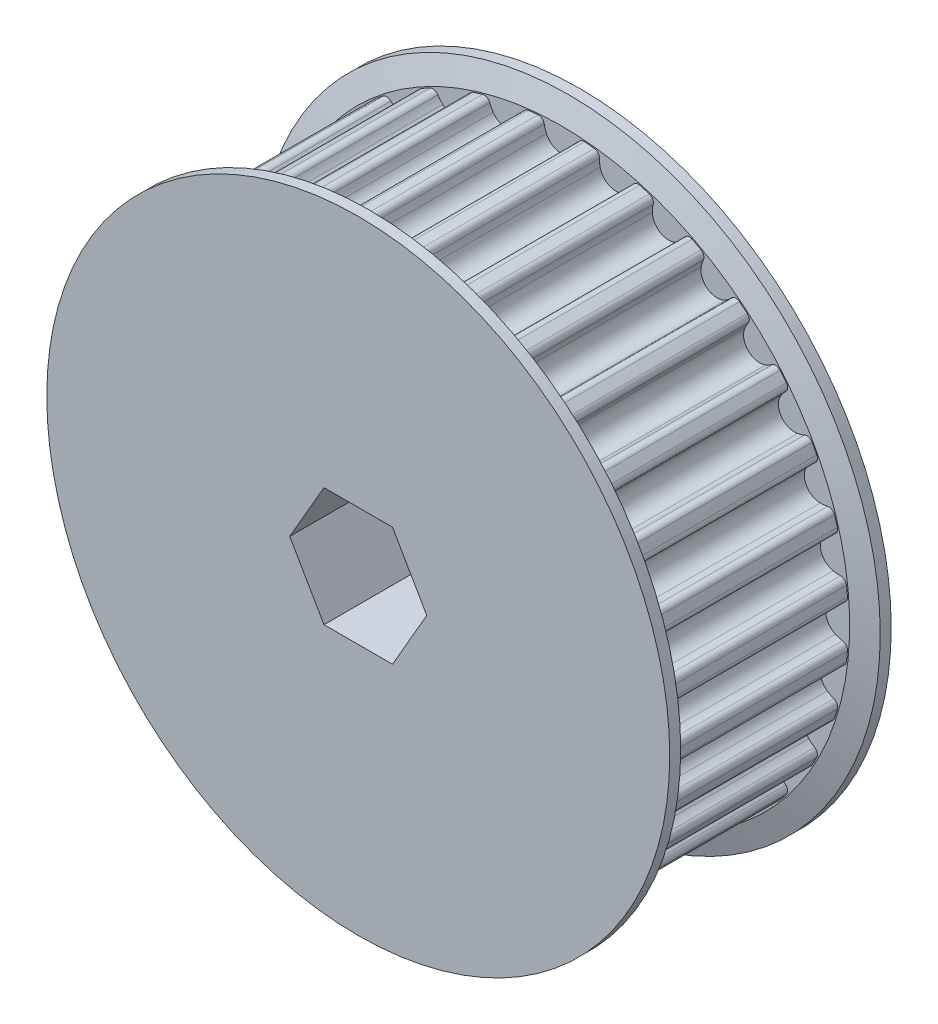
SolidWorks part; units mm, degrees
material "ABS"
ref_plane "Front" through (0, 0, 0) normal (0, 0, 1) x (1, 0, 0)
ref_plane "Top" through (0, 0, 0) normal (0, 1, 0) x (1, 0, 0)
ref_plane "Right" through (0, 0, 0) normal (1, 0, 0) x (0, 0, -1)
ref_plane "Plane1" through (0, 0, -1.6) normal (0, 0, 1) x (1, 0, 0)
sketch "Sketch1" plane through (0, 0, -1.6) normal (0, 0, 1) x (1, 0, 0)
  arc A0 (23.6907, -7.633) -> (23.9388, -6.8152) centre (0, 0) ccw
  arc A1 (23.9388, -6.8152) -> (23.6305, -6.2012) centre (23.4502, -6.6761) ccw
  arc A2 (23.6305, -6.2012) -> (23.0589, -5.9005) centre (24.5761, -3.7101) cw
  arc A3 (23.0589, -5.9005) -> (23.5616, -3.3729) centre (23.8587, -4.7458) cw
  arc A4 (23.5616, -3.3729) -> (24.2048, -3.3139) centre (24.1251, -5.9771) cw
  arc A5 (24.2048, -3.3139) -> (24.7246, -2.8646) centre (24.22, -2.8061) ccw
  arc A6 (24.7246, -2.8646) -> (24.8084, -2.014) centre (0, 0) ccw
  arc A7 (24.8084, -2.014) -> (24.3862, -1.4719) centre (24.302, -1.9729) ccw
  arc A8 (24.3862, -1.4719) -> (23.7669, -1.2885) centre (24.8277, 1.1557) cw
  arc A9 (23.7669, -1.2885) -> (23.7669, 1.2885) centre (24.3261, 0) cw
  arc A10 (23.7669, 1.2885) -> (24.3862, 1.4719) centre (24.8277, -1.1557) cw
  arc A11 (24.3862, 1.4719) -> (24.8084, 2.014) centre (24.302, 1.9729) ccw
  arc A12 (24.8084, 2.014) -> (24.7246, 2.8646) centre (0, 0) ccw
  arc A13 (24.7246, 2.8646) -> (24.2048, 3.3139) centre (24.22, 2.8061) ccw
  arc A14 (24.2048, 3.3139) -> (23.5616, 3.3729) centre (24.1251, 5.9771) cw
  arc A15 (23.5616, 3.3729) -> (23.0589, 5.9005) centre (23.8587, 4.7458) cw
  arc A16 (23.0589, 5.9005) -> (23.6305, 6.2012) centre (24.5761, 3.7101) cw
  arc A17 (23.6305, 6.2012) -> (23.9388, 6.8152) centre (23.4502, 6.6761) ccw
  arc A18 (23.9388, 6.8152) -> (23.6907, 7.633) centre (0, 0) ccw
  arc A19 (23.6907, 7.633) -> (23.0932, 7.9723) centre (23.2072, 7.4773) ccw
  arc A20 (23.0932, 7.9723) -> (22.4509, 7.9048) centre (22.4955, 10.5689) cw
  arc A21 (22.4509, 7.9048) -> (21.4647, 10.2856) centre (22.4744, 9.3092) cw
  arc A22 (21.4647, 10.2856) -> (21.9666, 10.6921) centre (23.38, 8.4334) cw
  arc A23 (21.9666, 10.6921) -> (22.1492, 11.3545) centre (21.6972, 11.1227) ccw
  arc A24 (22.1492, 11.3545) -> (21.7463, 12.1082) centre (0, 0) ccw
  arc A25 (21.7463, 12.1082) -> (21.0942, 12.3244) centre (21.3025, 11.8611) ccw
  arc A26 (21.0942, 12.3244) -> (20.4773, 12.1328) centre (20.0014, 14.7544) cw
  arc A27 (20.4773, 12.1328) -> (19.0456, 14.2756) centre (20.2264, 13.5149) cw
  arc A28 (19.0456, 14.2756) -> (19.4586, 14.7721) centre (21.2855, 12.8326) cw
  arc A29 (19.4586, 14.7721) -> (19.5085, 15.4574) centre (19.1103, 15.1419) ccw
  arc A30 (19.5085, 15.4574) -> (18.9663, 16.118) centre (0, 0) ccw
  arc A31 (18.9663, 16.118) -> (18.2845, 16.2028) centre (18.5792, 15.7891) ccw
  arc A32 (18.2845, 16.2028) -> (17.7169, 15.8946) centre (16.7386, 18.373) cw
  arc A33 (17.7169, 15.8946) -> (15.8946, 17.7169) centre (17.2012, 17.2012) cw
  arc A34 (15.8946, 17.7169) -> (16.2028, 18.2845) centre (18.373, 16.7386) cw
  arc A35 (16.2028, 18.2845) -> (16.118, 18.9663) centre (15.7891, 18.5792) ccw
  arc A36 (16.118, 18.9663) -> (15.4574, 19.5085) centre (0, 0) ccw
  arc A37 (15.4574, 19.5085) -> (14.7721, 19.4586) centre (15.1419, 19.1103) ccw
  arc A38 (14.7721, 19.4586) -> (14.2756, 19.0456) centre (12.8326, 21.2855) cw
  arc A39 (14.2756, 19.0456) -> (12.1328, 20.4773) centre (13.5149, 20.2264) cw
  arc A40 (12.1328, 20.4773) -> (12.3244, 21.0942) centre (14.7544, 20.0014) cw
  arc A41 (12.3244, 21.0942) -> (12.1082, 21.7463) centre (11.8611, 21.3025) ccw
  arc A42 (12.1082, 21.7463) -> (11.3545, 22.1492) centre (0, 0) ccw
  arc A43 (11.3545, 22.1492) -> (10.6921, 21.9666) centre (11.1227, 21.6972) ccw
  arc A44 (10.6921, 21.9666) -> (10.2856, 21.4647) centre (8.4334, 23.38) cw
  arc A45 (10.2856, 21.4647) -> (7.9048, 22.4509) centre (9.3092, 22.4744) cw
  arc A46 (7.9048, 22.4509) -> (7.9723, 23.0932) centre (10.5689, 22.4955) cw
  arc A47 (7.9723, 23.0932) -> (7.633, 23.6907) centre (7.4773, 23.2072) ccw
  arc A48 (7.633, 23.6907) -> (6.8152, 23.9388) centre (0, 0) ccw
  arc A49 (6.8152, 23.9388) -> (6.2012, 23.6305) centre (6.6761, 23.4502) ccw
  arc A50 (6.2012, 23.6305) -> (5.9005, 23.0589) centre (3.7101, 24.5761) cw
  arc A51 (5.9005, 23.0589) -> (3.3729, 23.5616) centre (4.7458, 23.8587) cw
  arc A52 (3.3729, 23.5616) -> (3.3139, 24.2048) centre (5.9771, 24.1251) cw
  arc A53 (3.3139, 24.2048) -> (2.8646, 24.7246) centre (2.8061, 24.22) ccw
  arc A54 (2.8646, 24.7246) -> (2.014, 24.8084) centre (0, 0) ccw
  arc A55 (2.014, 24.8084) -> (1.4719, 24.3862) centre (1.9729, 24.302) ccw
  arc A56 (1.4719, 24.3862) -> (1.2885, 23.7669) centre (-1.1557, 24.8277) cw
  arc A57 (1.2885, 23.7669) -> (-1.2885, 23.7669) centre (0, 24.3261) cw
  arc A58 (-1.2885, 23.7669) -> (-1.4719, 24.3862) centre (1.1557, 24.8277) cw
  arc A59 (-1.4719, 24.3862) -> (-2.014, 24.8084) centre (-1.9729, 24.302) ccw
  arc A60 (-2.014, 24.8084) -> (-2.8646, 24.7246) centre (0, 0) ccw
  arc A61 (-2.8646, 24.7246) -> (-3.3139, 24.2048) centre (-2.8061, 24.22) ccw
  arc A62 (-3.3139, 24.2048) -> (-3.3729, 23.5616) centre (-5.9771, 24.1251) cw
  arc A63 (-3.3729, 23.5616) -> (-5.9005, 23.0589) centre (-4.7458, 23.8587) cw
  arc A64 (-5.9005, 23.0589) -> (-6.2012, 23.6305) centre (-3.7101, 24.5761) cw
  arc A65 (-6.2012, 23.6305) -> (-6.8152, 23.9388) centre (-6.6761, 23.4502) ccw
  arc A66 (-6.8152, 23.9388) -> (-7.633, 23.6907) centre (0, 0) ccw
  arc A67 (-7.633, 23.6907) -> (-7.9723, 23.0932) centre (-7.4773, 23.2072) ccw
  arc A68 (-7.9723, 23.0932) -> (-7.9048, 22.4509) centre (-10.5689, 22.4955) cw
  arc A69 (-7.9048, 22.4509) -> (-10.2856, 21.4647) centre (-9.3092, 22.4744) cw
  arc A70 (-10.2856, 21.4647) -> (-10.6921, 21.9666) centre (-8.4334, 23.38) cw
  arc A71 (-10.6921, 21.9666) -> (-11.3545, 22.1492) centre (-11.1227, 21.6972) ccw
  arc A72 (-11.3545, 22.1492) -> (-12.1082, 21.7463) centre (0, 0) ccw
  arc A73 (-12.1082, 21.7463) -> (-12.3244, 21.0942) centre (-11.8611, 21.3025) ccw
  arc A74 (-12.3244, 21.0942) -> (-12.1328, 20.4773) centre (-14.7544, 20.0014) cw
  arc A75 (-12.1328, 20.4773) -> (-14.2756, 19.0456) centre (-13.5149, 20.2264) cw
  arc A76 (-14.2756, 19.0456) -> (-14.7721, 19.4586) centre (-12.8326, 21.2855) cw
  arc A77 (-14.7721, 19.4586) -> (-15.4574, 19.5085) centre (-15.1419, 19.1103) ccw
  arc A78 (-15.4574, 19.5085) -> (-16.118, 18.9663) centre (0, 0) ccw
  arc A79 (-16.118, 18.9663) -> (-16.2028, 18.2845) centre (-15.7891, 18.5792) ccw
  arc A80 (-16.2028, 18.2845) -> (-15.8946, 17.7169) centre (-18.373, 16.7386) cw
  arc A81 (-15.8946, 17.7169) -> (-17.7169, 15.8946) centre (-17.2012, 17.2012) cw
  arc A82 (-17.7169, 15.8946) -> (-18.2845, 16.2028) centre (-16.7386, 18.373) cw
  arc A83 (-18.2845, 16.2028) -> (-18.9663, 16.118) centre (-18.5792, 15.7891) ccw
  arc A84 (-18.9663, 16.118) -> (-19.5085, 15.4574) centre (0, 0) ccw
  arc A85 (-19.5085, 15.4574) -> (-19.4586, 14.7721) centre (-19.1103, 15.1419) ccw
  arc A86 (-19.4586, 14.7721) -> (-19.0456, 14.2756) centre (-21.2855, 12.8326) cw
  arc A87 (-19.0456, 14.2756) -> (-20.4773, 12.1328) centre (-20.2264, 13.5149) cw
  arc A88 (-20.4773, 12.1328) -> (-21.0942, 12.3244) centre (-20.0014, 14.7544) cw
  arc A89 (-21.0942, 12.3244) -> (-21.7463, 12.1082) centre (-21.3025, 11.8611) ccw
  arc A90 (-21.7463, 12.1082) -> (-22.1492, 11.3545) centre (0, 0) ccw
  arc A91 (-22.1492, 11.3545) -> (-21.9666, 10.6921) centre (-21.6972, 11.1227) ccw
  arc A92 (-21.9666, 10.6921) -> (-21.4647, 10.2856) centre (-23.38, 8.4334) cw
  arc A93 (-21.4647, 10.2856) -> (-22.4509, 7.9048) centre (-22.4744, 9.3092) cw
  arc A94 (-22.4509, 7.9048) -> (-23.0932, 7.9723) centre (-22.4955, 10.5689) cw
  arc A95 (-23.0932, 7.9723) -> (-23.6907, 7.633) centre (-23.2072, 7.4773) ccw
  arc A96 (-23.6907, 7.633) -> (-23.9388, 6.8152) centre (0, 0) ccw
  arc A97 (-23.9388, 6.8152) -> (-23.6305, 6.2012) centre (-23.4502, 6.6761) ccw
  arc A98 (-23.6305, 6.2012) -> (-23.0589, 5.9005) centre (-24.5761, 3.7101) cw
  arc A99 (-23.0589, 5.9005) -> (-23.5616, 3.3729) centre (-23.8587, 4.7458) cw
  arc A100 (-23.5616, 3.3729) -> (-24.2048, 3.3139) centre (-24.1251, 5.9771) cw
  arc A101 (-24.2048, 3.3139) -> (-24.7246, 2.8646) centre (-24.22, 2.8061) ccw
  arc A102 (-24.7246, 2.8646) -> (-24.8084, 2.014) centre (0, 0) ccw
  arc A103 (-24.8084, 2.014) -> (-24.3862, 1.4719) centre (-24.302, 1.9729) ccw
  arc A104 (-24.3862, 1.4719) -> (-23.7669, 1.2885) centre (-24.8277, -1.1557) cw
  arc A105 (-23.7669, 1.2885) -> (-23.7669, -1.2885) centre (-24.3261, 0) cw
  arc A106 (-23.7669, -1.2885) -> (-24.3862, -1.4719) centre (-24.8277, 1.1557) cw
  arc A107 (-24.3862, -1.4719) -> (-24.8084, -2.014) centre (-24.302, -1.9729) ccw
  arc A108 (-24.8084, -2.014) -> (-24.7246, -2.8646) centre (0, 0) ccw
  arc A109 (-24.7246, -2.8646) -> (-24.2048, -3.3139) centre (-24.22, -2.8061) ccw
  arc A110 (-24.2048, -3.3139) -> (-23.5616, -3.3729) centre (-24.1251, -5.9771) cw
  arc A111 (-23.5616, -3.3729) -> (-23.0589, -5.9005) centre (-23.8587, -4.7458) cw
  arc A112 (-23.0589, -5.9005) -> (-23.6305, -6.2012) centre (-24.5761, -3.7101) cw
  arc A113 (-23.6305, -6.2012) -> (-23.9388, -6.8152) centre (-23.4502, -6.6761) ccw
  arc A114 (-23.9388, -6.8152) -> (-23.6907, -7.633) centre (0, 0) ccw
  arc A115 (-23.6907, -7.633) -> (-23.0932, -7.9723) centre (-23.2072, -7.4773) ccw
  arc A116 (-23.0932, -7.9723) -> (-22.4509, -7.9048) centre (-22.4955, -10.5689) cw
  arc A117 (-22.4509, -7.9048) -> (-21.4647, -10.2856) centre (-22.4744, -9.3092) cw
  arc A118 (-21.4647, -10.2856) -> (-21.9666, -10.6921) centre (-23.38, -8.4334) cw
  arc A119 (-21.9666, -10.6921) -> (-22.1492, -11.3545) centre (-21.6972, -11.1227) ccw
  arc A120 (-22.1492, -11.3545) -> (-21.7463, -12.1082) centre (0, 0) ccw
  arc A121 (-21.7463, -12.1082) -> (-21.0942, -12.3244) centre (-21.3025, -11.8611) ccw
  arc A122 (-21.0942, -12.3244) -> (-20.4773, -12.1328) centre (-20.0014, -14.7544) cw
  arc A123 (-20.4773, -12.1328) -> (-19.0456, -14.2756) centre (-20.2264, -13.5149) cw
  arc A124 (-19.0456, -14.2756) -> (-19.4586, -14.7721) centre (-21.2855, -12.8326) cw
  arc A125 (-19.4586, -14.7721) -> (-19.5085, -15.4574) centre (-19.1103, -15.1419) ccw
  arc A126 (-19.5085, -15.4574) -> (-18.9663, -16.118) centre (0, 0) ccw
  arc A127 (-18.9663, -16.118) -> (-18.2845, -16.2028) centre (-18.5792, -15.7891) ccw
  arc A128 (-18.2845, -16.2028) -> (-17.7169, -15.8946) centre (-16.7386, -18.373) cw
  arc A129 (-17.7169, -15.8946) -> (-15.8946, -17.7169) centre (-17.2012, -17.2012) cw
  arc A130 (-15.8946, -17.7169) -> (-16.2028, -18.2845) centre (-18.373, -16.7386) cw
  arc A131 (-16.2028, -18.2845) -> (-16.118, -18.9663) centre (-15.7891, -18.5792) ccw
  arc A132 (-16.118, -18.9663) -> (-15.4574, -19.5085) centre (0, 0) ccw
  arc A133 (-15.4574, -19.5085) -> (-14.7721, -19.4586) centre (-15.1419, -19.1103) ccw
  arc A134 (-14.7721, -19.4586) -> (-14.2756, -19.0456) centre (-12.8326, -21.2855) cw
  arc A135 (-14.2756, -19.0456) -> (-12.1328, -20.4773) centre (-13.5149, -20.2264) cw
  arc A136 (-12.1328, -20.4773) -> (-12.3244, -21.0942) centre (-14.7544, -20.0014) cw
  arc A137 (-12.3244, -21.0942) -> (-12.1082, -21.7463) centre (-11.8611, -21.3025) ccw
  arc A138 (-12.1082, -21.7463) -> (-11.3545, -22.1492) centre (0, 0) ccw
  arc A139 (-11.3545, -22.1492) -> (-10.6921, -21.9666) centre (-11.1227, -21.6972) ccw
  arc A140 (-10.6921, -21.9666) -> (-10.2856, -21.4647) centre (-8.4334, -23.38) cw
  arc A141 (-10.2856, -21.4647) -> (-7.9048, -22.4509) centre (-9.3092, -22.4744) cw
  arc A142 (-7.9048, -22.4509) -> (-7.9723, -23.0932) centre (-10.5689, -22.4955) cw
  arc A143 (-7.9723, -23.0932) -> (-7.633, -23.6907) centre (-7.4773, -23.2072) ccw
  arc A144 (-7.633, -23.6907) -> (-6.8152, -23.9388) centre (0, 0) ccw
  arc A145 (-6.8152, -23.9388) -> (-6.2012, -23.6305) centre (-6.6761, -23.4502) ccw
  arc A146 (-6.2012, -23.6305) -> (-5.9005, -23.0589) centre (-3.7101, -24.5761) cw
  arc A147 (-5.9005, -23.0589) -> (-3.3729, -23.5616) centre (-4.7458, -23.8587) cw
  arc A148 (-3.3729, -23.5616) -> (-3.3139, -24.2048) centre (-5.9771, -24.1251) cw
  arc A149 (-3.3139, -24.2048) -> (-2.8646, -24.7246) centre (-2.8061, -24.22) ccw
  arc A150 (-2.8646, -24.7246) -> (-2.014, -24.8084) centre (0, 0) ccw
  arc A151 (-2.014, -24.8084) -> (-1.4719, -24.3862) centre (-1.9729, -24.302) ccw
  arc A152 (-1.4719, -24.3862) -> (-1.2885, -23.7669) centre (1.1557, -24.8277) cw
  arc A153 (-1.2885, -23.7669) -> (1.2885, -23.7669) centre (0, -24.3261) cw
  arc A154 (1.2885, -23.7669) -> (1.4719, -24.3862) centre (-1.1557, -24.8277) cw
  arc A155 (1.4719, -24.3862) -> (2.014, -24.8084) centre (1.9729, -24.302) ccw
  arc A156 (2.014, -24.8084) -> (2.8646, -24.7246) centre (0, 0) ccw
  arc A157 (2.8646, -24.7246) -> (3.3139, -24.2048) centre (2.8061, -24.22) ccw
  arc A158 (3.3139, -24.2048) -> (3.3729, -23.5616) centre (5.9771, -24.1251) cw
  arc A159 (3.3729, -23.5616) -> (5.9005, -23.0589) centre (4.7458, -23.8587) cw
  arc A160 (5.9005, -23.0589) -> (6.2012, -23.6305) centre (3.7101, -24.5761) cw
  arc A161 (6.2012, -23.6305) -> (6.8152, -23.9388) centre (6.6761, -23.4502) ccw
  arc A162 (6.8152, -23.9388) -> (7.633, -23.6907) centre (0, 0) ccw
  arc A163 (7.633, -23.6907) -> (7.9723, -23.0932) centre (7.4773, -23.2072) ccw
  arc A164 (7.9723, -23.0932) -> (7.9048, -22.4509) centre (10.5689, -22.4955) cw
  arc A165 (7.9048, -22.4509) -> (10.2856, -21.4647) centre (9.3092, -22.4744) cw
  arc A166 (10.2856, -21.4647) -> (10.6921, -21.9666) centre (8.4334, -23.38) cw
  arc A167 (10.6921, -21.9666) -> (11.3545, -22.1492) centre (11.1227, -21.6972) ccw
  arc A168 (11.3545, -22.1492) -> (12.1082, -21.7463) centre (0, 0) ccw
  arc A169 (12.1082, -21.7463) -> (12.3244, -21.0942) centre (11.8611, -21.3025) ccw
  arc A170 (12.3244, -21.0942) -> (12.1328, -20.4773) centre (14.7544, -20.0014) cw
  arc A171 (12.1328, -20.4773) -> (14.2756, -19.0456) centre (13.5149, -20.2264) cw
  arc A172 (14.2756, -19.0456) -> (14.7721, -19.4586) centre (12.8326, -21.2855) cw
  arc A173 (14.7721, -19.4586) -> (15.4574, -19.5085) centre (15.1419, -19.1103) ccw
  arc A174 (15.4574, -19.5085) -> (16.118, -18.9663) centre (0, 0) ccw
  arc A175 (16.118, -18.9663) -> (16.2028, -18.2845) centre (15.7891, -18.5792) ccw
  arc A176 (16.2028, -18.2845) -> (15.8946, -17.7169) centre (18.373, -16.7386) cw
  arc A177 (15.8946, -17.7169) -> (17.7169, -15.8946) centre (17.2012, -17.2012) cw
  arc A178 (17.7169, -15.8946) -> (18.2845, -16.2028) centre (16.7386, -18.373) cw
  arc A179 (18.2845, -16.2028) -> (18.9663, -16.118) centre (18.5792, -15.7891) ccw
  arc A180 (18.9663, -16.118) -> (19.5085, -15.4574) centre (0, 0) ccw
  arc A181 (19.5085, -15.4574) -> (19.4586, -14.7721) centre (19.1103, -15.1419) ccw
  arc A182 (19.4586, -14.7721) -> (19.0456, -14.2756) centre (21.2855, -12.8326) cw
  arc A183 (19.0456, -14.2756) -> (20.4773, -12.1328) centre (20.2264, -13.5149) cw
  arc A184 (20.4773, -12.1328) -> (21.0942, -12.3244) centre (20.0014, -14.7544) cw
  arc A185 (21.0942, -12.3244) -> (21.7463, -12.1082) centre (21.3025, -11.8611) ccw
  arc A186 (21.7463, -12.1082) -> (22.1492, -11.3545) centre (0, 0) ccw
  arc A187 (22.1492, -11.3545) -> (21.9666, -10.6921) centre (21.6972, -11.1227) ccw
  arc A188 (21.9666, -10.6921) -> (21.4647, -10.2856) centre (23.38, -8.4334) cw
  arc A189 (21.4647, -10.2856) -> (22.4509, -7.9048) centre (22.4744, -9.3092) cw
  arc A190 (22.4509, -7.9048) -> (23.0932, -7.9723) centre (22.4955, -10.5689) cw
  arc A191 (23.0932, -7.9723) -> (23.6907, -7.633) centre (23.2072, -7.4773) ccw
extrude "Boss-Extrude1" add sketch "Sketch1" against normal blind 16
ref_plane "Plane2" through (0, 0, -17.6) normal (0, 0, 1) x (1, 0, 0)
sketch "Sketch2" plane through (0, 0, -17.6) normal (0, 0, 1) x (1, 0, 0)
  circle A0 centre (0, 0) radius 27
extrude "Boss-Extrude2" add sketch "Sketch2" against normal blind 1.6
ref_plane "Plane3" through (0, 0, -1.6) normal (0, 0, -1) x (-1, 0, 0)
sketch "Sketch3" plane through (0, 0, -1.6) normal (0, 0, -1) x (-1, 0, 0)
  circle A0 centre (0, 0) radius 27
extrude "Boss-Extrude3" add sketch "Sketch3" against normal blind 1.6
chamfer "Chamfer1" distance 2 angle 18 1 edges at (27, 0, -1.6)
chamfer "Chamfer2" distance 2 angle 18 1 edges at (-27, 0, -17.6)
sketch "Sketch12" plane through (0, 0, -19.2) normal (0, 0, -1) x (-1, 0, 0)
  line L1 (2.9696, -5.1435) -> (5.9392, 0)
  line L2 (5.9392, 0) -> (2.9696, 5.1435)
  line L3 (2.9696, 5.1435) -> (-2.9696, 5.1435)
  line L4 (-2.9696, 5.1435) -> (-5.9392, 0)
  line L5 (-5.9392, 0) -> (-2.9696, -5.1435)
  line L6 (-2.9696, -5.1435) -> (2.9696, -5.1435)
  circle A0 centre (0, 0) radius 5.1435 construction
  dimension "D1" = 10.287
extrude "Cut-Extrude6" cut sketch "Sketch12" against normal through all
